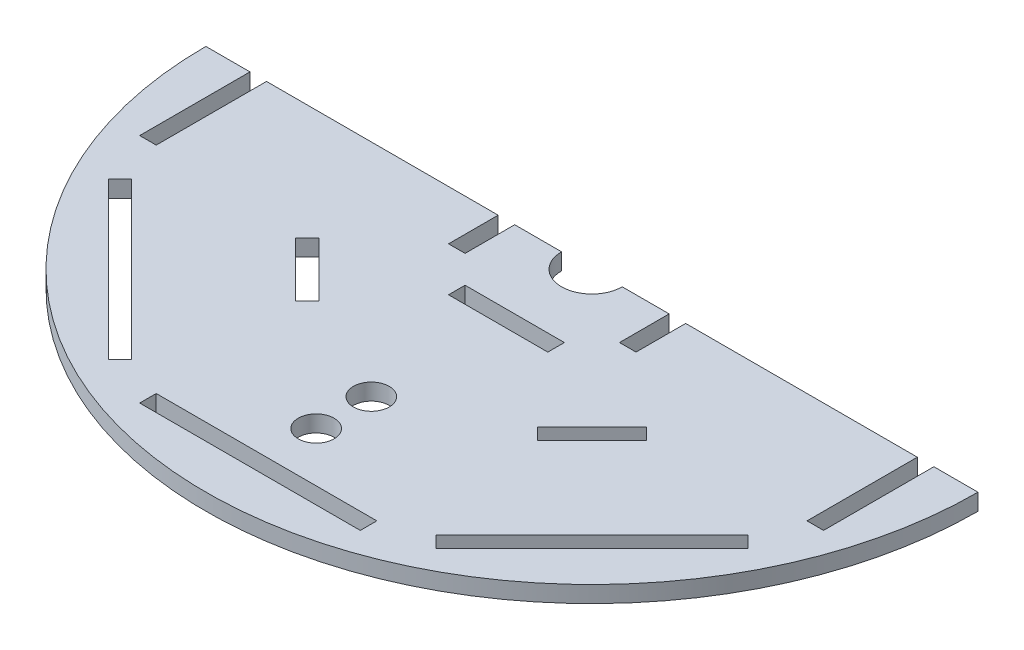
SolidWorks part; units mm, degrees
ref_plane "Alzado" through (0, 0, 0) normal (0, 0, 1) x (1, 0, 0)
ref_plane "Planta" through (0, 0, 0) normal (0, 1, 0) x (1, 0, 0)
ref_plane "Vista lateral" through (0, 0, 0) normal (1, 0, 0) x (0, 0, -1)
sketch "Croquis1" plane through (0, 0, 0) normal (0, 1, 0) x (1, 0, 0)
  line L0 (-59, 0) -> (-17, 0)
  line L1 (-14, 0) -> (-5.5, 0)
  line L2 (5.5, 0) -> (14, 0)
  line L3 (62, 0) -> (70, 0)
  line L4 (17, 0) -> (59, 0)
  line L5 (24.7487, -24.7487) -> (19.799, -29.6985)
  line L6 (19.799, -29.6985) -> (21.9203, -31.8198)
  line L7 (21.9203, -31.8198) -> (31.8198, -21.9203)
  line L8 (29.6985, -19.799) -> (31.8198, -21.9203)
  line L9 (24.7487, -24.7487) -> (29.6985, -19.799)
  line L13 (-24.7487, -24.7487) -> (-29.6985, -19.799)
  line L14 (-29.6985, -19.799) -> (-31.8198, -21.9203)
  line L15 (-31.8198, -21.9203) -> (-21.9203, -31.8198)
  line L16 (-19.799, -29.6985) -> (-21.9203, -31.8198)
  line L17 (-24.7487, -24.7487) -> (-19.799, -29.6985)
  line L18 (0, -5.5) -> (0, -50) construction
  line L19 (-70, 0) -> (-62, 0)
  line L22 (-17, 0) -> (-17, -9)
  line L26 (-17, -9) -> (-14, -9)
  line L27 (-14, -9) -> (-14, 0)
  line L33 (14, -9) -> (17, -9)
  line L34 (14, 0) -> (14, -9)
  line L37 (17, -9) -> (17, 0)
  line L38 (-9, -14) -> (-9, -17)
  line L39 (0, -14) -> (-9, -14)
  line L40 (9, -14) -> (0, -14)
  line L52 (59, -20) -> (59, 0)
  line L55 (62, 0) -> (62, -20)
  line L56 (62, -20) -> (59, -20)
  line L57 (27.5772, -55.8614) -> (55.8614, -27.5772)
  line L58 (55.8614, -27.5772) -> (57.9828, -29.6985)
  line L59 (57.9828, -29.6985) -> (43.8406, -43.8406)
  line L60 (43.8406, -43.8406) -> (29.6985, -57.9828)
  line L61 (29.6985, -57.9828) -> (27.5772, -55.8614)
  line L62 (-20, -59) -> (20, -59)
  line L63 (20, -59) -> (20, -62)
  line L64 (20, -62) -> (0, -62)
  line L65 (0, -62) -> (-20, -62)
  line L66 (-20, -62) -> (-20, -59)
  line L67 (-55.8614, -27.5772) -> (-27.5772, -55.8614)
  line L68 (-27.5772, -55.8614) -> (-29.6985, -57.9828)
  line L69 (-29.6985, -57.9828) -> (-43.8406, -43.8406)
  line L70 (-43.8406, -43.8406) -> (-57.9828, -29.6985)
  line L71 (-57.9828, -29.6985) -> (-55.8614, -27.5772)
  line L72 (-59, 0) -> (-59, -20)
  line L73 (-59, -20) -> (-62, -20)
  line L74 (-62, -20) -> (-62, 0)
  line L82 (9, -17) -> (9, -14)
  line L83 (-9, -17) -> (9, -17)
  line L87 (9, 17) -> (-9, 17) [skipped]
  line L88 (-9, 14) -> (0, 14) [skipped]
  line L89 (-9, 17) -> (-9, 14) [skipped]
  line L90 (14, 9) -> (14, 0) [skipped]
  line L96 (17, 9) -> (14, 9) [skipped]
  arc A0 (-5.5, 0) -> (5.5, 0) centre (0, 0) ccw
  circle A1 centre (0, -50) radius 3.25
  arc A2 (-70, 0) -> (70, 0) centre (0, 0) ccw
  circle A3 centre (0, -40) radius 3.25
  point P26 (0, 0)
  point P47 (0, 0)
  point P88 (0, 0)
  point P92 (0, 0)
  dimension "D7" = 6.5
  dimension "D21" = 6.5
  dimension "D6" = 50
  dimension "D8" = 14
  dimension "D14" = 4
  dimension "D20" = 40
extrude "Saliente-Extruir1" add sketch "Croquis1" along normal blind 3
